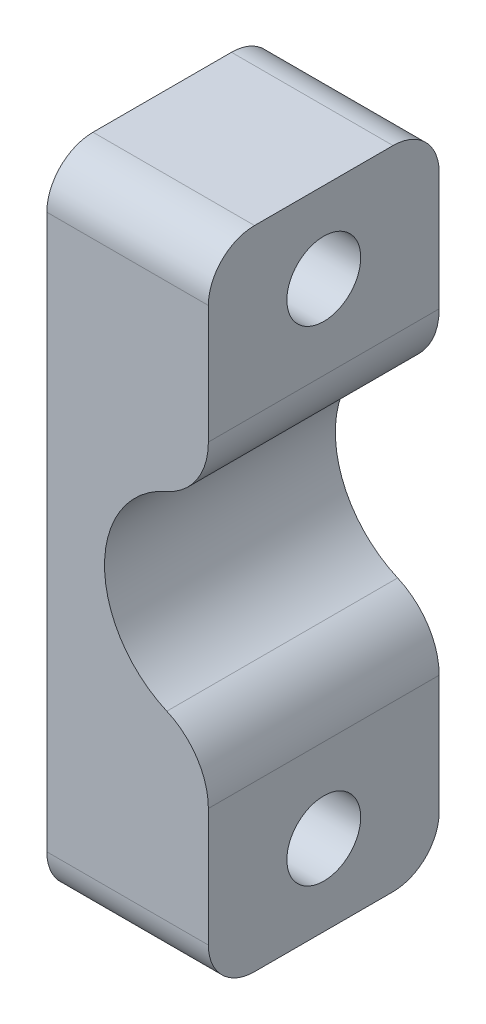
SolidWorks part; units mm, degrees
ref_plane "Front Plane" through (0, 0, 0) normal (0, 0, 1) x (1, 0, 0)
ref_plane "Top Plane" through (0, 0, 0) normal (0, 1, 0) x (1, 0, 0)
ref_plane "Right Plane" through (0, 0, 0) normal (1, 0, 0) x (0, 0, -1)
sketch "Sketch1" plane through (0, 0, 0) normal (0, 0, 1) x (1, 0, 0)
  line L1 (-6, -3) -> (6, -3)
  line L2 (-6, -3) -> (-6, 3)
  line L3 (-6, 3) -> (6, 3)
  line L4 (6, -3) -> (6, 3)
  line L5 (-6, -3) -> (6, 3) construction
  line L6 (-6, 3) -> (6, -3) construction
  line L7 (-6, -0.9) -> (6, -0.9)
  line L8 (-6, -0.9) -> (-6, 0.9)
  line L9 (-6, 0.9) -> (6, 0.9)
  line L10 (6, -0.9) -> (6, 0.9)
  line L11 (-6, -0.9) -> (6, 0.9) construction
  line L12 (-6, 0.9) -> (6, -0.9) construction
  point P0 (0, 0)
  point P6 (0, 0)
  dimension "D1" = 1.8
  dimension "D2" = 12
  dimension "D3" = 6
extrude "Boss-Extrude1" add sketch "Sketch1" along normal mid plane 6 contours L2 L9 L4 L3 | L7 L2 L1 L4
sketch "Sketch2" plane through (0, 0, 3) normal (0, 0, 1) x (1, 0, 0)
  line L1 (6, 3) -> (10, 3)
  line L2 (6, 3) -> (6, -3)
  line L3 (6, -3) -> (10, -3)
  line L4 (10, 3) -> (10, -3)
  dimension "D1" = 6
  dimension "D2" = 4
extrude "Boss-Extrude2" add sketch "Sketch2" against normal blind 6 separate body
sketch "Sketch3" plane through (0, 0, 0) normal (0, 0, 1) x (1, 0, 0)
  line L1 (9.8883, 14) -> (16.8883, 14)
  line L2 (9.8883, 14) -> (9.8883, -14)
  line L3 (9.8883, -14) -> (16.8883, -14)
  line L4 (16.8883, 14) -> (16.8883, -14)
  point P4 (9.8883, 0)
  dimension "D1" = 28
  dimension "D2" = 7
extrude "Boss-Extrude3" add sketch "Sketch3" along normal mid plane 10
sketch "Sketch5" plane through (0, 0, 5) normal (0, 0, 1) x (1, 0, 0)
  line L0 (16.8883, -14) -> (16.8883, 14) construction
  circle A0 centre (16.8883, 0) radius 4.5
  dimension "D1" = 9
extrude "Cut-Extrude1" cut sketch "Sketch5" against normal through all both and the other way through all
fillet "Fillet1" radius 3 4 edges at (16.8883, 4.5, 0) (16.8883, -4.5, 0) (9.8883, -3, 0) (9.8883, 3, 0)
fillet "Fillet2" radius 2 4 edges at (13.3883, 14, -5) (13.3883, -14, -5) (13.3883, -14, 5) (13.3883, 14, 5)
sketch "Sketch6" plane through (16.8883, 0, 0) normal (1, 0, 0) x (0, 0, -1)
  line L0 (-3, 14) -> (3, 14) construction
  line L1 (-3, -14) -> (3, -14) construction
  circle A0 centre (0, 10.5) radius 1.6
  circle A1 centre (0, -10.5) radius 1.6
  dimension "D1" = 3.2
  dimension "D2" = 3.2
  dimension "D4" = 3.5
  dimension "D3" = 3.5
extrude "Cut-Extrude2" cut sketch "Sketch6" against normal blind 16
sketch "Sketch7" plane through (0, 0, 5) normal (0, 0, 1) x (1, 0, 0)
  line L1 (9.8883, 12) -> (-8.2192, 12)
  line L2 (9.8883, 12) -> (9.8883, -9.7717)
  line L3 (9.8883, -9.7717) -> (-8.2192, -9.7717)
  line L4 (-8.2192, 12) -> (-8.2192, -9.7717)
extrude "Cut-Extrude3" cut sketch "Sketch7" against normal blind 30
